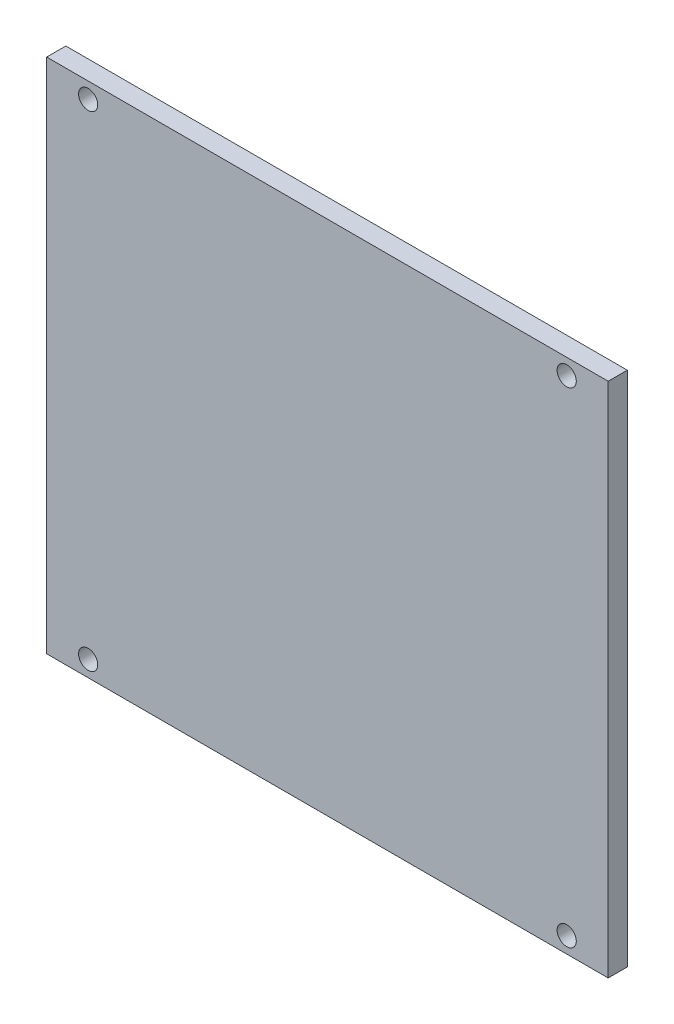
SolidWorks part; units mm, degrees
ref_plane "Front Plane" through (0, 0, 0) normal (0, 0, 1) x (1, 0, 0)
ref_plane "Top Plane" through (0, 0, 0) normal (0, 1, 0) x (1, 0, 0)
ref_plane "Right Plane" through (0, 0, 0) normal (1, 0, 0) x (0, 0, -1)
sketch "Sketch1" plane through (0, 0, 0) normal (0, 0, 1) x (1, 0, 0)
  line L1 (-44, -40.5) -> (44, -40.5)
  line L2 (-44, -40.5) -> (-44, 40.5)
  line L3 (-44, 40.5) -> (44, 40.5)
  line L4 (44, -40.5) -> (44, 40.5)
  line L5 (-44, -40.5) -> (44, 40.5) construction
  line L6 (-44, 40.5) -> (44, -40.5) construction
  point P0 (0, 0)
  dimension "D1" = 88
  dimension "D2" = 81
extrude "Boss-Extrude1" add sketch "Sketch1" along normal blind 3
sketch "Sketch2" plane through (0, 0, 0) normal (0, 0, -1) x (-1, 0, 0)
  line L0 (29.9223, 34.2905) -> (12.4223, 34.2905) construction
  line L1 (29.9223, 34.2905) -> (29.9223, 20.4905) construction
  line L2 (29.9223, 20.4905) -> (12.4223, 20.4905) construction
  line L3 (12.4223, 34.2905) -> (12.4223, 20.4905) construction
  line L4 (29.9223, 34.2905) -> (12.4223, 20.4905) construction
  line L5 (29.9223, 20.4905) -> (12.4223, 34.2905) construction
  circle A0 centre (12.4223, 20.4905) radius 0.5
  circle A1 centre (12.4223, 34.2905) radius 0.5
  circle A2 centre (29.9223, 34.2905) radius 0.5
  circle A3 centre (29.9223, 20.4905) radius 0.5
  circle A4 centre (12.4223, 20.4905) radius 3
  circle A5 centre (29.9223, 20.4905) radius 3
  circle A6 centre (12.4223, 34.2905) radius 3
  circle A7 centre (29.9223, 34.2905) radius 3
  point P0 (21.1723, 27.3905)
  dimension "D3" = 1
  dimension "D4" = 6
  dimension "D1" = 17.5
  dimension "D2" = 13.8
extrude "regulator" add sketch "Sketch2" along normal blind 3
sketch "Sketch3" plane through (0, 0, 0) normal (0, 0, -1) x (-1, 0, 0)
  line L0 (-44, -40.5) -> (-44, 40.5) construction
  circle A0 centre (-23, 24.8592) radius 1.5
  circle A1 centre (-22.5522, -17.1384) radius 1.5
  circle A2 centre (-23, 24.8592) radius 4
  circle A3 centre (-22.5522, -17.1384) radius 4
  dimension "D2" = 3
  dimension "D3" = 8
  dimension "D1" = 42
  dimension "D4" = 21
extrude "arduiono" add sketch "Sketch3" along normal blind 3
sketch "Sketch4" plane through (0, 0, 0) normal (0, 0, -1) x (-1, 0, 0)
  line L0 (36.5091, -11.7589) -> (-1.2453, -11.7589)
  line L1 (36.5091, -11.7589) -> (36.5091, -7.5579)
  line L2 (36.5091, -7.5579) -> (-1.2453, -7.5579)
  line L3 (-1.2453, -11.7589) -> (-1.2453, -7.5579)
  circle A0 centre (36.2722, -20.196) radius 0.5
  circle A1 centre (22.6722, -20.196) radius 0.5
  circle A2 centre (36.2722, -20.196) radius 3
  circle A3 centre (22.6722, -20.196) radius 3
  circle A4 centre (12.6788, -19.8324) radius 0.5
  circle A5 centre (-0.9212, -19.8324) radius 0.5
  circle A6 centre (12.6788, -19.8324) radius 3
  circle A7 centre (-0.9212, -19.8324) radius 3
  dimension "D1" = 1
  dimension "D2" = 6
  dimension "D3" = 13.6
  dimension "D4" = 10
extrude "relay" add sketch "Sketch4" along normal blind 3
sketch "Sketch5" plane through (0, 0, 0) normal (0, 0, -1) x (-1, 0, 0)
  line L1 (-37.5, -38) -> (37.5, -38) construction
  line L2 (-37.5, -38) -> (-37.5, 38) construction
  line L3 (-37.5, 38) -> (37.5, 38) construction
  line L4 (37.5, -38) -> (37.5, 38) construction
  line L5 (-37.5, -38) -> (37.5, 38) construction
  line L6 (-37.5, 38) -> (37.5, -38) construction
  circle A0 centre (-37.5, 38) radius 1.5
  circle A1 centre (37.5, 38) radius 1.5
  circle A2 centre (37.5, -38) radius 1.5
  circle A3 centre (-37.5, -38) radius 1.5
  point P0 (0, 0)
  dimension "D1" = 3
  dimension "D2" = 75
  dimension "D3" = 76
extrude "Cut-Extrude1" cut sketch "Sketch5" against normal through all
